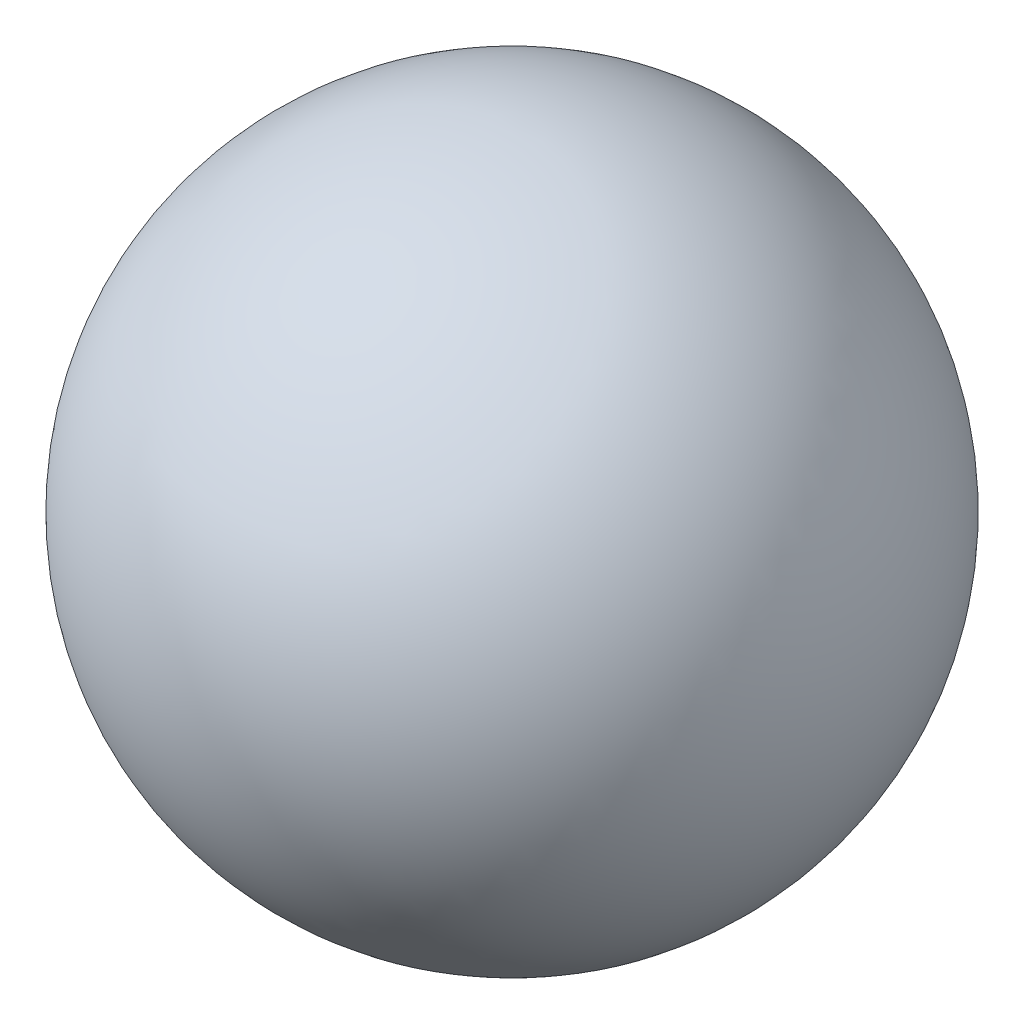
SolidWorks part; units mm, degrees
ref_plane "前视基准面" through (0, 0, 0) normal (0, 0, 1) x (1, 0, 0)
ref_plane "上视基准面" through (0, 0, 0) normal (0, 1, 0) x (1, 0, 0)
ref_plane "右视基准面" through (0, 0, 0) normal (1, 0, 0) x (0, 0, -1)
sketch "草图1" plane through (0, 0, 0) normal (0, 0, 1) x (1, 0, 0)
  line L0 (0, 37.5) -> (0, -37.5)
  arc A1 (0, 37.5) -> (0, -37.5) centre (0, 0) ccw
revolve "旋转4" add sketch "草图1" angle 360 about L0
